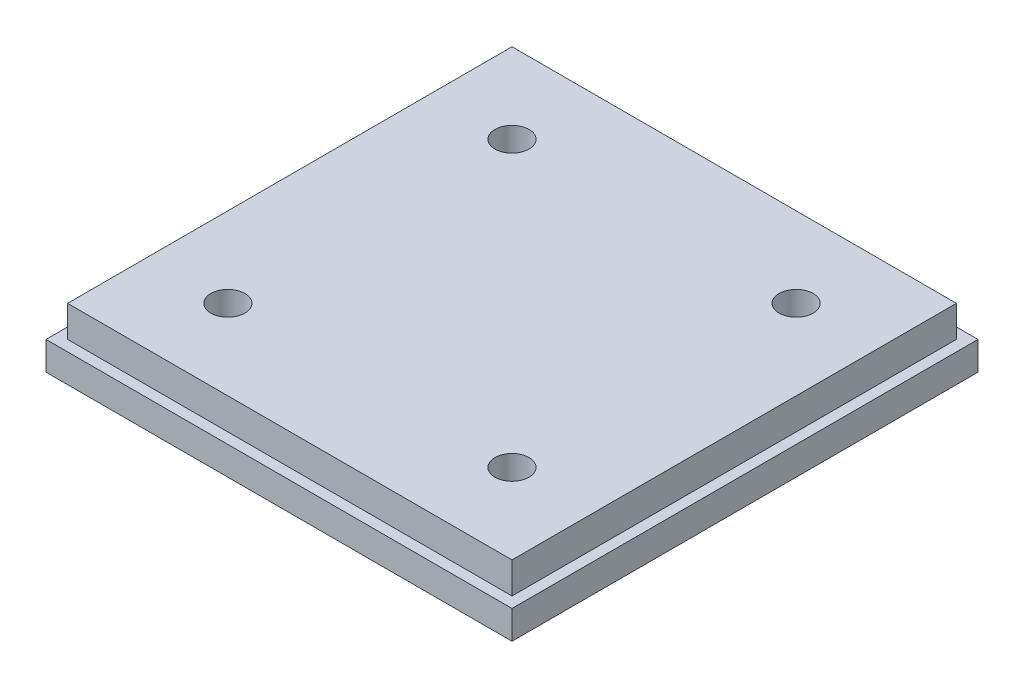
SolidWorks part; units mm, degrees
ref_plane "Front Plane" through (0, 0, 0) normal (0, 0, 1) x (1, 0, 0)
ref_plane "Top Plane" through (0, 0, 0) normal (0, 1, 0) x (1, 0, 0)
ref_plane "Right Plane" through (0, 0, 0) normal (1, 0, 0) x (0, 0, -1)
sketch "Sketch1" plane through (0, 0, 0) normal (0, 1, 0) x (1, 0, 0)
  line L1 (-41, 41) -> (41, 41)
  line L2 (-41, 41) -> (-41, -41)
  line L3 (-41, -41) -> (41, -41)
  line L4 (41, 41) -> (41, -41)
  line L5 (-41, 41) -> (41, -41) construction
  line L6 (-41, -41) -> (41, 41) construction
  point P0 (0, 0)
  dimension "D1" = 82
  dimension "D2" = 82
extrude "Boss-Extrude1" add sketch "Sketch1" along normal blind 5
sketch "Sketch2" plane through (0, 5, 0) normal (0, 1, 0) x (1, 0, 0)
  line L8 (39.1, -39.1) -> (39.1, 39.1)
  line L9 (39.1, 39.1) -> (-39.1, 39.1)
  line L10 (-39.1, 39.1) -> (-39.1, -39.1)
  line L11 (-39.1, -39.1) -> (39.1, -39.1)
  line L12 (39.1, -39.1) -> (39.1, 39.1)
  line L13 (39.1, 39.1) -> (-39.1, 39.1)
  line L14 (-39.1, 39.1) -> (-39.1, -39.1)
  line L15 (-39.1, -39.1) -> (39.1, -39.1)
  dimension "D1" = 1.9
extrude "Boss-Extrude2" add sketch "Sketch2" along normal blind 5.5
sketch "Sketch3" plane through (0, 10.5, 0) normal (0, 1, 0) x (1, 0, 0)
  line L0 (0, 39.1) -> (0, -39.1) construction
  line L1 (39.1, 39.1) -> (-39.1, 39.1) construction
  line L2 (-39.1, -39.1) -> (39.1, -39.1) construction
  line L3 (-39.1, 0) -> (39.1, 0) construction
  line L4 (-39.1, 39.1) -> (-39.1, -39.1) construction
  line L5 (39.1, -39.1) -> (39.1, 39.1) construction
  circle A0 centre (-25, 25) radius 3
  circle A1 centre (-25, -25) radius 3
  circle A2 centre (25, -25) radius 3
  circle A3 centre (25, 25) radius 3
  dimension "D1" = 6
  dimension "D2" = 25
  dimension "D3" = 25
extrude "Cut-Extrude1" cut sketch "Sketch3" against normal blind 8
